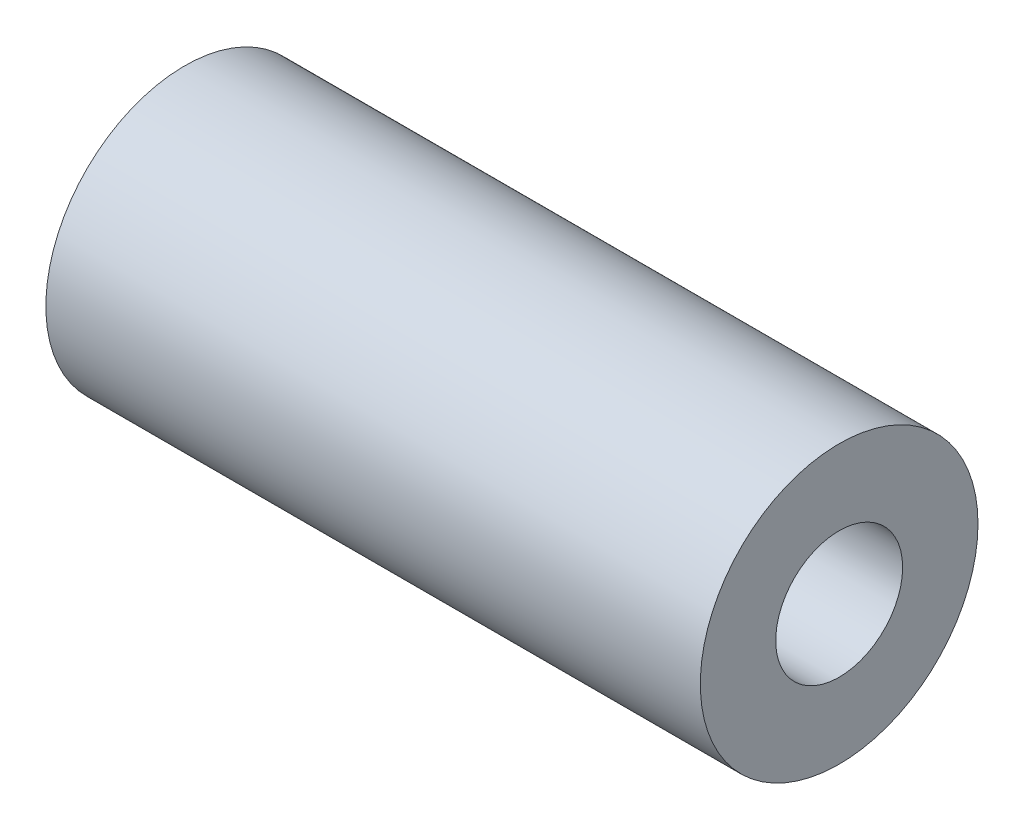
SolidWorks part; units mm, degrees
ref_plane "Front Plane" through (0, 0, 0) normal (0, 0, 1) x (1, 0, 0)
ref_plane "Top Plane" through (0, 0, 0) normal (0, 1, 0) x (1, 0, 0)
ref_plane "Right Plane" through (0, 0, 0) normal (1, 0, 0) x (0, 0, -1)
sketch "Sketch1" plane through (0, 0, 0) normal (1, 0, 0) x (0, 0, -1)
  circle A0 centre (0, 0) radius 1.6
  circle A1 centre (0, 0) radius 3.5
  dimension "D1" = 3.2
  dimension "D2" = 7
extrude "Boss-Extrude1" add sketch "Sketch1" along normal blind 16.5
